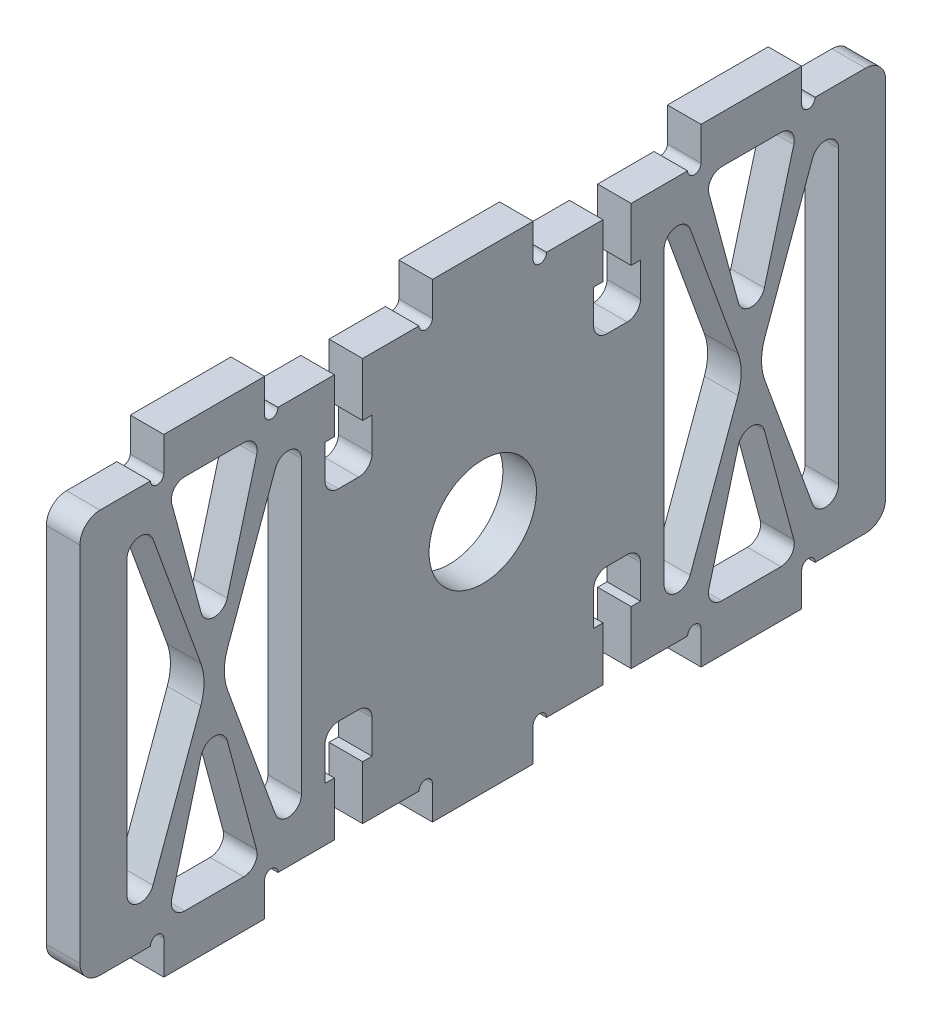
SolidWorks part; units mm, degrees
ref_plane "前视基准面" through (0, 0, 0) normal (0, 0, 1) x (1, 0, 0)
ref_plane "上视基准面" through (0, 0, 0) normal (0, 1, 0) x (1, 0, 0)
ref_plane "右视基准面" through (0, 0, 0) normal (1, 0, 0) x (0, 0, -1)
other "Configuration Table"
sketch "草图1" plane through (0, 0, 0) normal (1, 0, 0) x (0, 0, -1)
  line L1 (60, -30) -> (-60, -30)
  line L2 (60, -30) -> (60, 30)
  line L3 (60, 30) -> (-60, 30)
  line L4 (-60, -30) -> (-60, 30)
  line L5 (60, -30) -> (-60, 30) construction
  line L6 (60, 30) -> (-60, -30) construction
  point P0 (0, 0)
  dimension "D1" = 60
  dimension "D2" = 120
extrude "凸台-拉伸1" add sketch "草图1" along normal blind 5
sketch "草图2" plane through (5, 0, 0) normal (1, 0, 0) x (0, 0, -1)
  circle A0 centre (0, 0) radius 8
  dimension "D1" = 16
extrude "切除-拉伸1" cut sketch "草图2" against normal mid plane 10
sketch "草图3" plane through (5, 0, 0) normal (1, 0, 0) x (0, 0, -1)
  line L0 (0, 45) -> (0, 0) construction
  line L2 (-7.5, 30) -> (-7.5, 35)
  line L3 (60, 30) -> (-60, 30) construction
  line L4 (-7.5, 35) -> (7.5, 35)
  line L5 (7.5, 35) -> (7.5, 30)
  line L6 (7.5, 30) -> (-7.5, 30)
  line L7 (-32.5, 30) -> (-47.5, 30)
  line L8 (-47.5, 30) -> (-47.5, 35)
  line L9 (-47.5, 35) -> (-32.5, 35)
  line L10 (-32.5, 35) -> (-32.5, 30)
  line L11 (7.5, 30) -> (-32.5, 30) construction
  line L12 (32.5, 35) -> (32.5, 30)
  line L13 (47.5, 35) -> (32.5, 35)
  line L14 (47.5, 30) -> (47.5, 35)
  line L15 (32.5, 30) -> (47.5, 30)
  line L16 (-5.0949, 0) -> (4.5252, 0) construction
  line L17 (7.5, -30) -> (-32.5, -30) construction
  line L18 (32.5, -30) -> (47.5, -30)
  line L19 (47.5, -30) -> (47.5, -35)
  line L20 (47.5, -35) -> (32.5, -35)
  line L21 (32.5, -35) -> (32.5, -30)
  line L22 (-32.5, -35) -> (-32.5, -30)
  line L23 (-47.5, -35) -> (-32.5, -35)
  line L24 (-47.5, -30) -> (-47.5, -35)
  line L25 (-32.5, -30) -> (-47.5, -30)
  line L26 (7.5, -30) -> (-7.5, -30)
  line L27 (7.5, -35) -> (7.5, -30)
  line L28 (-7.5, -35) -> (7.5, -35)
  line L29 (-7.5, -30) -> (-7.5, -35)
  dimension "D1" = 5
  dimension "D2" = 15
  dimension "D4" = 40
  dimension "D3" = 2
extrude "凸台-拉伸2" add sketch "草图3" against normal blind 5
sketch "草图4" plane through (5, 0, 0) normal (1, 0, 0) x (0, 0, -1)
  line L0 (-20, 30) -> (-20, -30) construction
  line L1 (-7.5, 30) -> (-32.5, 30) construction
  line L2 (-32.5, -30) -> (-7.5, -30) construction
  line L3 (-22.1, 30) -> (-22.1, 22)
  line L4 (-22.1, 22) -> (-23.5, 22)
  line L5 (-23.5, 22) -> (-23.5, 15)
  line L6 (-23.5, 15) -> (-16.5, 15)
  line L7 (-22.1, 30) -> (-17.9, 30)
  line L8 (-16.5, 22) -> (-16.5, 15)
  line L9 (-17.9, 22) -> (-16.5, 22)
  line L10 (-17.9, 30) -> (-17.9, 22)
  line L11 (0, 35) -> (0, 18.2193) construction
  line L12 (7.5, 35) -> (-7.5, 35) construction
  line L13 (17.9, 30) -> (17.9, 22)
  line L14 (17.9, 22) -> (16.5, 22)
  line L15 (16.5, 22) -> (16.5, 15)
  line L16 (22.1, 30) -> (17.9, 30)
  line L17 (23.5, 15) -> (16.5, 15)
  line L18 (23.5, 22) -> (23.5, 15)
  line L19 (22.1, 22) -> (23.5, 22)
  line L20 (22.1, 30) -> (22.1, 22)
  line L21 (-3.3727, 0) -> (3.7275, 0) construction
  line L22 (0, -35) -> (0, -18.2193) construction
  line L23 (22.1, -30) -> (22.1, -22)
  line L24 (22.1, -22) -> (23.5, -22)
  line L25 (23.5, -22) -> (23.5, -15)
  line L26 (23.5, -15) -> (16.5, -15)
  line L27 (22.1, -30) -> (17.9, -30)
  line L28 (16.5, -22) -> (16.5, -15)
  line L29 (17.9, -22) -> (16.5, -22)
  line L30 (17.9, -30) -> (17.9, -22)
  line L31 (-17.9, -30) -> (-17.9, -22)
  line L32 (-17.9, -22) -> (-16.5, -22)
  line L33 (-16.5, -22) -> (-16.5, -15)
  line L34 (-22.1, -30) -> (-17.9, -30)
  line L35 (-23.5, -15) -> (-16.5, -15)
  line L36 (-23.5, -22) -> (-23.5, -15)
  line L37 (-22.1, -22) -> (-23.5, -22)
  line L38 (-22.1, -30) -> (-22.1, -22)
  point P13 (-20, 15)
  point P28 (20, 15)
  point P49 (20, -15)
  point P50 (-20, -15)
  dimension "D1" = 3.5
  dimension "D2" = 2.1
  dimension "D3" = 8
  dimension "D4" = 15
extrude "切除-拉伸2" cut sketch "草图4" against normal blind 5
sketch "草图5" plane through (5, 0, 0) normal (1, 0, 0) x (0, 0, -1)
  line L0 (-53, 28) -> (-27, 28) construction
  line L1 (-27, 28) -> (-27, -28) construction
  line L2 (-27, -28) -> (-53, -28) construction
  line L3 (-53, -28) -> (-53, 28) construction
  line L4 (0, -3.6785) -> (0, 21.2485) construction
  line L5 (-10.8219, 0) -> (24.0759, 0) construction
  line L6 (-40, 28) -> (-40, -28) construction
  line L7 (-53, 0) -> (-27, 0) construction
  line L8 (-46.3216, 25.4801) -> (-41.9312, 9.1731)
  line L9 (-38.0688, 9.1731) -> (-33.6784, 25.4801)
  line L10 (-35.6097, 28) -> (-44.3903, 28)
  line L11 (-49.1204, 22.3311) -> (-41.9942, 2.7339)
  line L12 (-41.9942, -2.7339) -> (-49.1204, -22.3311)
  line L13 (-53, -21.6477) -> (-53, 21.6477)
  line L14 (-38.0688, -9.1731) -> (-33.6784, -25.4801)
  line L15 (-46.3216, -25.4801) -> (-41.9312, -9.1731)
  line L16 (-35.6097, -28) -> (-44.3903, -28)
  line L17 (-38.0058, -2.7339) -> (-30.8796, -22.3311)
  line L18 (-30.8796, 22.3311) -> (-38.0058, 2.7339)
  line L19 (-27, -21.6477) -> (-27, 21.6477)
  line L20 (53, 0) -> (27, 0) construction
  line L21 (40, 28) -> (40, -28) construction
  line L22 (53, -28) -> (53, 28) construction
  line L23 (27, -28) -> (53, -28) construction
  line L24 (27, 28) -> (27, -28) construction
  line L25 (53, 28) -> (27, 28) construction
  line L26 (27, -21.6477) -> (27, 21.6477)
  line L27 (30.8796, 22.3311) -> (38.0058, 2.7339)
  line L28 (38.0058, -2.7339) -> (30.8796, -22.3311)
  line L29 (35.6097, -28) -> (44.3903, -28)
  line L30 (46.3216, -25.4801) -> (41.9312, -9.1731)
  line L31 (38.0688, -9.1731) -> (33.6784, -25.4801)
  line L32 (53, -21.6477) -> (53, 21.6477)
  line L33 (41.9942, -2.7339) -> (49.1204, -22.3311)
  line L34 (49.1204, 22.3311) -> (41.9942, 2.7339)
  line L35 (35.6097, 28) -> (44.3903, 28)
  line L36 (38.0688, 9.1731) -> (33.6784, 25.4801)
  line L37 (46.3216, 25.4801) -> (41.9312, 9.1731)
  arc A0 (-41.9312, 9.1731) -> (-38.0688, 9.1731) centre (-40, 9.6931) ccw
  arc A1 (-33.6784, 25.4801) -> (-35.6097, 28) centre (-35.6097, 26) ccw
  arc A2 (-46.3216, 25.4801) -> (-44.3903, 28) centre (-44.3903, 26) cw
  arc A3 (-41.9942, 2.7339) -> (-41.9942, -2.7339) centre (-49.5125, 0) cw
  arc A4 (-49.1204, -22.3311) -> (-53, -21.6477) centre (-51, -21.6477) cw
  arc A5 (-49.1204, 22.3311) -> (-53, 21.6477) centre (-51, 21.6477) ccw
  arc A6 (-41.9312, -9.1731) -> (-38.0688, -9.1731) centre (-40, -9.6931) cw
  arc A7 (-33.6784, -25.4801) -> (-35.6097, -28) centre (-35.6097, -26) cw
  arc A8 (-46.3216, -25.4801) -> (-44.3903, -28) centre (-44.3903, -26) ccw
  arc A9 (-38.0058, 2.7339) -> (-38.0058, -2.7339) centre (-30.4875, 0) ccw
  arc A10 (-30.8796, -22.3311) -> (-27, -21.6477) centre (-29, -21.6477) ccw
  arc A11 (-30.8796, 22.3311) -> (-27, 21.6477) centre (-29, 21.6477) cw
  arc A12 (30.8796, 22.3311) -> (27, 21.6477) centre (29, 21.6477) ccw
  arc A13 (30.8796, -22.3311) -> (27, -21.6477) centre (29, -21.6477) cw
  arc A14 (38.0058, 2.7339) -> (38.0058, -2.7339) centre (30.4875, 0) cw
  arc A15 (46.3216, -25.4801) -> (44.3903, -28) centre (44.3903, -26) cw
  arc A16 (33.6784, -25.4801) -> (35.6097, -28) centre (35.6097, -26) ccw
  arc A17 (41.9312, -9.1731) -> (38.0688, -9.1731) centre (40, -9.6931) ccw
  arc A18 (49.1204, 22.3311) -> (53, 21.6477) centre (51, 21.6477) cw
  arc A19 (49.1204, -22.3311) -> (53, -21.6477) centre (51, -21.6477) ccw
  arc A20 (41.9942, 2.7339) -> (41.9942, -2.7339) centre (49.5125, 0) ccw
  arc A21 (46.3216, 25.4801) -> (44.3903, 28) centre (44.3903, 26) ccw
  arc A22 (33.6784, 25.4801) -> (35.6097, 28) centre (35.6097, 26) cw
  arc A23 (41.9312, 9.1731) -> (38.0688, 9.1731) centre (40, 9.6931) cw
  point P21 (-40, 2)
  point P24 (-33, 28)
  point P27 (-47, 28)
  point P30 (-41, 0)
  point P33 (-53, -33)
  point P36 (-53, 33)
  point P99 (53, 33)
  point P100 (53, -33)
  point P101 (41, 0)
  point P102 (47, 28)
  point P103 (33, 28)
  point P104 (40, 2)
  dimension "D8" = 2
  dimension "D9" = 8
  dimension "D10" = 2
  dimension "D1" = 40
  dimension "D2" = 26
  dimension "D3" = 56
  dimension "D4" = 14
  dimension "D5" = 2
  dimension "D6" = 66
  dimension "D7" = 1
extrude "切除-拉伸3" cut sketch "草图5" against normal blind 10
fillet "圆角1" radius 3 4 edges at (2.5, 30, -60) (2.5, -30, -60) (2.5, -30, 60) (2.5, 30, 60)
sketch "草图6" plane through (5, 0, 0) normal (1, 0, 0) x (0, 0, -1)
  line L0 (-47.5, 30) -> (-57, 30) construction
  line L1 (-49.5, 30) -> (-47.5, 30)
  line L2 (-32.5, 30) -> (-30.5, 30)
  line L3 (-22.1, 30) -> (-32.5, 30) construction
  line L4 (-9.5, 30) -> (-7.5, 30)
  line L5 (7.5, 30) -> (9.5, 30)
  line L6 (30.5, 30) -> (32.5, 30)
  line L7 (47.5, 30) -> (49.5, 30)
  line L8 (-47.5, 30) -> (-7.5, 30) construction
  line L9 (-3.3832, 0) -> (4.8686, 0) construction
  line L10 (-47.5, -30) -> (-7.5, -30) construction
  line L11 (47.5, -30) -> (49.5, -30)
  line L12 (30.5, -30) -> (32.5, -30)
  line L13 (7.5, -30) -> (9.5, -30)
  line L14 (-9.5, -30) -> (-7.5, -30)
  line L15 (-32.5, -30) -> (-30.5, -30)
  line L16 (-49.5, -30) -> (-47.5, -30)
  arc A0 (-47.5, 30) -> (-49.5, 30) centre (-48.5, 30) cw
  arc A1 (-32.5, 30) -> (-30.5, 30) centre (-31.5, 30) ccw
  arc A2 (-7.5, 30) -> (-9.5, 30) centre (-8.5, 30) cw
  arc A3 (7.5, 30) -> (9.5, 30) centre (8.5, 30) ccw
  arc A4 (32.5, 30) -> (30.5, 30) centre (31.5, 30) cw
  arc A5 (47.5, 30) -> (49.5, 30) centre (48.5, 30) ccw
  arc A6 (47.5, -30) -> (49.5, -30) centre (48.5, -30) cw
  arc A7 (32.5, -30) -> (30.5, -30) centre (31.5, -30) ccw
  arc A8 (7.5, -30) -> (9.5, -30) centre (8.5, -30) cw
  arc A9 (-7.5, -30) -> (-9.5, -30) centre (-8.5, -30) ccw
  arc A10 (-32.5, -30) -> (-30.5, -30) centre (-31.5, -30) cw
  arc A11 (-47.5, -30) -> (-49.5, -30) centre (-48.5, -30) ccw
  dimension "D1" = 1
  dimension "D2" = 1
  dimension "D4" = 40
  dimension "D3" = 3
extrude "切除-拉伸4" cut sketch "草图6" against normal blind 10
fillet "圆角2" radius 2 8 edges at (2.5, -15, -23.5) (2.5, -15, -16.5) (2.5, -15, 23.5) (2.5, -15, 16.5) (2.5, 15, -23.5) (2.5, 15, -16.5) (2.5, 15, 16.5) (2.5, 15, 23.5)
sketch "草图7" plane through (5, 0, 0) normal (1, 0, 0) x (0, 0, -1)
